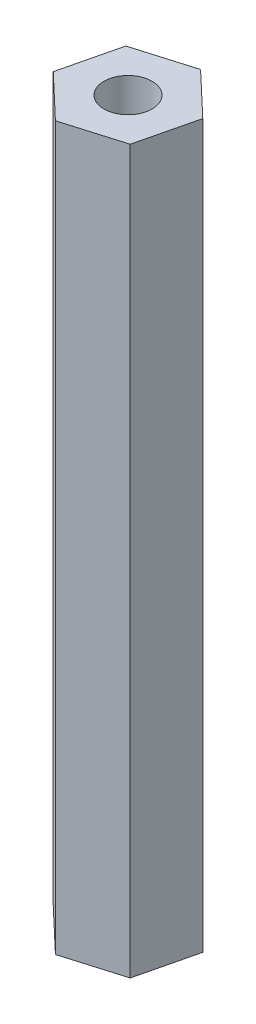
SolidWorks part; units mm, degrees
material "Alloy Steel"
ref_plane "Front Plane" through (0, 0, 0) normal (0, 0, 1) x (1, 0, 0)
ref_plane "Top Plane" through (0, 0, 0) normal (0, 1, 0) x (1, 0, 0)
ref_plane "Right Plane" through (0, 0, 0) normal (1, 0, 0) x (0, 0, -1)
sketch "Sketch1" plane through (0, 0, 0) normal (0, 1, 0) x (1, 0, 0)
  line L1 (3.625, -3.4437) -> (4.7949, 1.4175)
  line L2 (4.7949, 1.4175) -> (1.1699, 4.8612)
  line L3 (1.1699, 4.8612) -> (-3.625, 3.4437)
  line L4 (-3.625, 3.4437) -> (-4.7949, -1.4175)
  line L5 (-4.7949, -1.4175) -> (-1.1699, -4.8612)
  line L6 (-1.1699, -4.8612) -> (3.625, -3.4437)
  circle A0 centre (0, 0) radius 4.3301 construction
  dimension "D1" = 10
extrude "Extrude-Thin1" add sketch "Sketch1" along normal blind 60 thin thin type one direction reverse wall 2
sketch "Sketch2" plane through (0, 60, 0) normal (0, 1, 0) x (1, 0, 0)
  circle A0 centre (0, 0) radius 2
  dimension "D1" = 4
extrude "Extrude-Thin2" add sketch "Sketch2" against normal blind 60 thin
